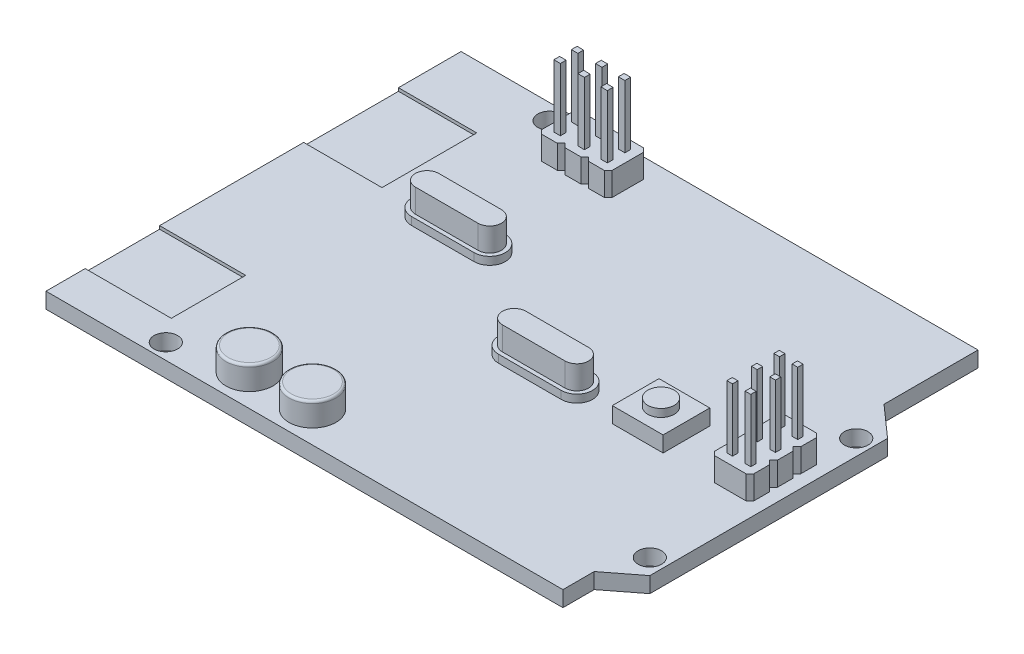
SolidWorks part; units mm, degrees
ref_plane "Front Plane" through (0, 0, 0) normal (0, 0, 1) x (1, 0, 0)
ref_plane "Top Plane" through (0, 0, 0) normal (0, 1, 0) x (1, 0, 0)
ref_plane "Right Plane" through (0, 0, 0) normal (1, 0, 0) x (0, 0, -1)
sketch "Sketch1" plane through (0, 0, 0) normal (0, 1, 0) x (1, 0, 0)
  line L0 (0, 0) -> (66, 0)
  line L1 (66, 0) -> (66, 4)
  line L2 (70, 7.1009) -> (70, 37.4502)
  line L3 (70, 37.4502) -> (66, 41)
  line L4 (66, 41) -> (66, 53)
  line L5 (66, 53) -> (0, 53)
  line L6 (0, 53) -> (0, 0)
  line L7 (66, 4) -> (70, 7.1009)
  point P4 (70, 7.1009)
  point P9 (70, 37.4502)
  dimension "D1" = 53
  dimension "D2" = 66
  dimension "D3" = 12
  dimension "D4" = 4
  dimension "D5" = 4
  dimension "D6" = 4
extrude "Boss-Extrude1" add sketch "Sketch1" along normal blind 2
sketch "Sketch2" plane through (0, 0, 0) normal (0, 1, 0) x (1, 0, 0)
  line L0 (70, 7.1009) -> (70, 37.4502) construction
  line L1 (0, 53) -> (0, 0) construction
  line L2 (0, 0) -> (66, 0) construction
  line L4 (66, 53) -> (0, 53) construction
  circle A0 centre (68, 35.4502) radius 1.5
  circle A1 centre (68, 9.1009) radius 1.5
  circle A2 centre (13.3, 2) radius 1.5
  circle A3 centre (13.3, 51) radius 1.5
  point P10 (0, 0)
  point P11 (0, 0)
  point P16 (0, 0)
  point P22 (0, 0)
  dimension "D1" = 3
  dimension "D4" = 3
  dimension "D5" = 3
  dimension "D6" = 3
  dimension "D2" = 2
  dimension "D3" = 2
  dimension "D7" = 13.3
  dimension "D8" = 2
  dimension "D9" = 2
  dimension "D10" = 2
  dimension "D11" = 2
  dimension "D12" = 13.3
extrude "Cut-Extrude2" cut sketch "Sketch2" against normal through all and the other way through all
sketch "Sketch3" plane through (0, 0, 0) normal (0, 1, 0) x (1, 0, 0)
  line L0 (0, 53) -> (0, 0) construction
  line L1 (0, 45) -> (10, 45)
  line L2 (0, 45) -> (0, 32.9)
  line L3 (0, 32.9) -> (10, 32.9)
  line L4 (10, 45) -> (10, 32.9)
  line L5 (66, 53) -> (0, 53) construction
  line L6 (0, 14.5) -> (11, 14.5)
  line L7 (0, 14.5) -> (0, 5)
  line L8 (0, 5) -> (11, 5)
  line L9 (11, 14.5) -> (11, 5)
  line L10 (0, 0) -> (66, 0) construction
  dimension "D1" = 10
  dimension "D2" = 12.1
  dimension "D3" = 8
  dimension "D4" = 11
  dimension "D5" = 9.5
  dimension "D6" = 5
extrude "Cut-Extrude7" cut sketch "Sketch3" against normal blind 0.4 from surface at 2 starting at face at (68, 2, -7.6009)
sketch "Sketch4" plane through (0, 2, 0) normal (0, 1, 0) x (1, 0, 0)
  line L0 (63.8799, 30.5) -> (63.3799, 30)
  line L1 (63.8799, 30.5) -> (67.8799, 30.5)
  line L2 (63.3799, 30) -> (63.3799, 28)
  line L3 (63.8799, 27.5) -> (67.8799, 27.5)
  line L4 (68.3799, 30) -> (68.3799, 28)
  line L5 (63.3799, 28) -> (63.8799, 27.5)
  line L6 (67.8799, 30.5) -> (68.3799, 30)
  line L7 (68.3799, 28) -> (67.8799, 27.5)
  line L8 (66, 53) -> (0, 53) construction
  line L9 (70, 7.1009) -> (70, 37.4502) construction
  point P12 (0, 0)
  point P13 (0, 0)
  dimension "D1" = 22.5
  dimension "D2" = 1.6201
extrude "Boss-Extrude2" add sketch "Sketch4" along normal blind 3
pattern_linear "LPattern1" count 3 spacing 3 along (0, 0, 1) of "Boss-Extrude2"
sketch "Sketch5" plane through (0, 5, 0) normal (0, 1, 0) x (1, 0, 0)
  line L0 (65.8799, 30.5) -> (65.8799, 26.0273) construction
  line L1 (64.3546, 29.2687) -> (65.0788, 29.2687)
  line L2 (64.3546, 29.2687) -> (64.3546, 28.579)
  line L3 (64.3546, 28.579) -> (65.0788, 28.579)
  line L4 (65.0788, 29.2687) -> (65.0788, 28.579)
  line L5 (67.8799, 30.5) -> (63.8799, 30.5) construction
  line L6 (63.8799, 27.5) -> (67.8799, 27.5) construction
  line L7 (66.681, 29.2687) -> (66.681, 28.579)
  line L8 (67.4052, 28.579) -> (66.681, 28.579)
  line L9 (67.4052, 29.2687) -> (67.4052, 28.579)
  line L10 (67.4052, 29.2687) -> (66.681, 29.2687)
  line L11 (67.4052, 25.7313) -> (66.681, 25.7313)
  line L12 (67.4052, 25.7313) -> (67.4052, 26.421)
  line L13 (67.4052, 26.421) -> (66.681, 26.421)
  line L14 (66.681, 25.7313) -> (66.681, 26.421)
  line L15 (65.0788, 25.7313) -> (65.0788, 26.421)
  line L16 (64.3546, 26.421) -> (65.0788, 26.421)
  line L17 (64.3546, 25.7313) -> (64.3546, 26.421)
  line L18 (64.3546, 25.7313) -> (65.0788, 25.7313)
  line L19 (63.8799, 24.5) -> (67.8799, 24.5) construction
  line L20 (66.681, 23.2687) -> (66.681, 22.579)
  line L21 (67.4052, 22.579) -> (66.681, 22.579)
  line L22 (67.4052, 23.2687) -> (67.4052, 22.579)
  line L23 (67.4052, 23.2687) -> (66.681, 23.2687)
  line L24 (64.3546, 23.2687) -> (65.0788, 23.2687)
  line L25 (64.3546, 23.2687) -> (64.3546, 22.579)
  line L26 (64.3546, 22.579) -> (65.0788, 22.579)
  line L27 (65.0788, 23.2687) -> (65.0788, 22.579)
extrude "Boss-Extrude4" add sketch "Sketch5" along normal blind 8
sketch "Sketch6" plane through (0, 2, 0) normal (0, 1, 0) x (1, 0, 0)
  line L0 (66, 53) -> (0, 53) construction
  line L1 (17.2829, 51) -> (19.2829, 51)
  line L2 (16.7829, 50.5) -> (16.7829, 46.5)
  line L3 (17.2829, 46) -> (19.2829, 46)
  line L4 (19.7829, 50.5) -> (19.7829, 46.5)
  line L5 (17.2829, 51) -> (16.7829, 50.5)
  line L6 (19.2829, 51) -> (19.7829, 50.5)
  line L7 (16.7829, 46.5) -> (17.2829, 46)
  line L8 (19.7829, 46.5) -> (19.2829, 46)
  point P14 (0, 0)
  point P15 (0, 0)
  point P18 (0, 0)
  dimension "D3" = 2
extrude "Boss-Extrude5" add sketch "Sketch6" along normal blind 3
pattern_linear "LPattern3" count 3 spacing 3 along (1, 0, 0) of "Boss-Extrude5"
sketch "Sketch8" plane through (0, 5, 0) normal (0, 1, 0) x (1, 0, 0)
  line L0 (16.7829, 48.5) -> (25.7829, 48.5) construction
  line L1 (16.7829, 50.5) -> (16.7829, 46.5) construction
  line L2 (25.7829, 46.5) -> (25.7829, 50.5) construction
  line L3 (19.7829, 50.5) -> (19.7829, 47.7652) construction
  line L4 (22.7829, 50.5) -> (22.7829, 47.637) construction
  line L5 (20.9065, 49.9848) -> (20.9065, 49.2538)
  line L6 (17.8296, 49.9848) -> (18.6593, 49.9848)
  line L7 (17.8296, 49.9848) -> (17.8296, 49.2538)
  line L8 (17.8296, 49.2538) -> (18.6593, 49.2538)
  line L9 (18.6593, 49.9848) -> (18.6593, 49.2538)
  line L10 (21.7363, 49.2538) -> (20.9065, 49.2538)
  line L11 (21.7363, 49.9848) -> (21.7363, 49.2538)
  line L12 (21.7363, 49.9848) -> (20.9065, 49.9848)
  line L13 (23.8296, 49.9848) -> (24.6593, 49.9848)
  line L14 (23.8296, 49.9848) -> (23.8296, 49.2538)
  line L15 (23.8296, 49.2538) -> (24.6593, 49.2538)
  line L16 (24.6593, 49.9848) -> (24.6593, 49.2538)
  line L17 (24.6593, 47.0152) -> (24.6593, 47.7462)
  line L18 (23.8296, 47.7462) -> (24.6593, 47.7462)
  line L19 (23.8296, 47.0152) -> (23.8296, 47.7462)
  line L20 (23.8296, 47.0152) -> (24.6593, 47.0152)
  line L21 (21.7363, 47.0152) -> (20.9065, 47.0152)
  line L22 (21.7363, 47.0152) -> (21.7363, 47.7462)
  line L23 (21.7363, 47.7462) -> (20.9065, 47.7462)
  line L24 (20.9065, 47.0152) -> (20.9065, 47.7462)
  line L25 (18.6593, 47.0152) -> (18.6593, 47.7462)
  line L26 (17.8296, 47.7462) -> (18.6593, 47.7462)
  line L27 (17.8296, 47.0152) -> (17.8296, 47.7462)
  line L28 (17.8296, 47.0152) -> (18.6593, 47.0152)
extrude "Boss-Extrude6" add sketch "Sketch8" along normal blind 8
sketch "Sketch9" plane through (0, 2, 0) normal (0, 1, 0) x (1, 0, 0)
  line L0 (63.8799, 21.5) -> (67.8799, 21.5) construction
  line L1 (50.8024, 27.4638) -> (57.2894, 27.4638)
  line L2 (50.8024, 27.4638) -> (50.8024, 21.5)
  line L3 (50.8024, 21.5) -> (57.2894, 21.5)
  line L4 (57.2894, 27.4638) -> (57.2894, 21.5)
extrude "Boss-Extrude7" add sketch "Sketch9" along normal blind 2
sketch "Sketch11" plane through (0, 4, 0) normal (0, 1, 0) x (1, 0, 0)
  circle A0 centre (54.0459, 24.4819) radius 1.6805
extrude "Boss-Extrude8" add sketch "Sketch11" along normal blind 1
sketch "Sketch12" plane through (0, 2, 0) normal (0, 1, 0) x (1, 0, 0)
  line L0 (36.8597, 22.9198) -> (44.8597, 22.9198) construction
  line L1 (36.8597, 24.9198) -> (44.8597, 24.9198)
  line L2 (36.8597, 20.9198) -> (44.8597, 20.9198)
  arc A0 (36.8597, 24.9198) -> (36.8597, 20.9198) centre (36.8597, 22.9198) ccw
  arc A1 (44.8597, 20.9198) -> (44.8597, 24.9198) centre (44.8597, 22.9198) ccw
  point P2 (40.8597, 22.9198)
  point P7 (40.8597, 22.9198)
  dimension "D1" = 8
  dimension "D2" = 4
extrude "Boss-Extrude9" add sketch "Sketch12" along normal blind 1
sketch "Sketch13" plane through (0, 3, 0) normal (0, 1, 0) x (1, 0, 0)
  line L4 (36.8597, 10.9198) -> (44.8597, 10.9198)
  line L5 (44.8597, 34.9198) -> (36.8597, 34.9198)
  line L6 (36.8597, 10.9198) -> (44.8597, 10.9198)
  line L7 (44.8597, 34.9198) -> (36.8597, 34.9198)
  line L10 (44.8597, 24.4198) -> (36.8597, 24.4198)
  line L11 (36.8597, 21.4198) -> (44.8597, 21.4198)
  line L12 (44.8597, 24.4198) -> (36.8597, 24.4198)
  line L13 (36.8597, 21.4198) -> (44.8597, 21.4198)
  arc A4 (36.8597, 34.9198) -> (36.8597, 10.9198) centre (36.8597, 22.9198) ccw
  arc A5 (44.8597, 10.9198) -> (44.8597, 34.9198) centre (44.8597, 22.9198) ccw
  arc A6 (36.8597, 34.9198) -> (36.8597, 10.9198) centre (36.8597, 22.9198) ccw
  arc A7 (44.8597, 10.9198) -> (44.8597, 34.9198) centre (44.8597, 22.9198) ccw
  arc A10 (44.8597, 21.4198) -> (44.8597, 24.4198) centre (44.8597, 22.9198) ccw
  arc A11 (36.8597, 24.4198) -> (36.8597, 21.4198) centre (36.8597, 22.9198) ccw
  arc A12 (44.8597, 21.4198) -> (44.8597, 24.4198) centre (44.8597, 22.9198) ccw
  arc A13 (36.8597, 24.4198) -> (36.8597, 21.4198) centre (36.8597, 22.9198) ccw
  dimension "D1" = 10
  dimension "D2" = 0.5
extrude "Boss-Extrude10" add sketch "Sketch13" along normal blind 3 contours L12 A13 L13 A12
sketch "Sketch14" plane through (0, 2, 0) normal (0, 1, 0) x (1, 0, 0)
  line L0 (16.0597, 32.5953) -> (24.0597, 32.5953) construction
  line L1 (16.0597, 34.5953) -> (24.0597, 34.5953)
  line L2 (16.0597, 30.5953) -> (24.0597, 30.5953)
  arc A0 (16.0597, 34.5953) -> (16.0597, 30.5953) centre (16.0597, 32.5953) ccw
  arc A1 (24.0597, 30.5953) -> (24.0597, 34.5953) centre (24.0597, 32.5953) ccw
  point P2 (20.0597, 32.5953)
  dimension "D1" = 8
  dimension "D2" = 4
extrude "Boss-Extrude11" add sketch "Sketch14" along normal blind 1
sketch "Sketch15" plane through (0, 3, 0) normal (0, 1, 0) x (1, 0, 0)
  line L0 (16.0597, 31.0953) -> (24.0597, 31.0953)
  line L1 (24.0597, 34.0953) -> (16.0597, 34.0953)
  line L2 (16.0597, 30.5953) -> (24.0597, 30.5953)
  line L3 (24.0597, 34.5953) -> (16.0597, 34.5953)
  line L4 (16.0597, 30.5953) -> (24.0597, 30.5953)
  line L5 (24.0597, 34.5953) -> (16.0597, 34.5953)
  arc A0 (16.0597, 34.0953) -> (16.0597, 31.0953) centre (16.0597, 32.5953) ccw
  arc A1 (24.0597, 31.0953) -> (24.0597, 34.0953) centre (24.0597, 32.5953) ccw
  arc A2 (16.0597, 34.5953) -> (16.0597, 30.5953) centre (16.0597, 32.5953) ccw
  arc A3 (24.0597, 30.5953) -> (24.0597, 34.5953) centre (24.0597, 32.5953) ccw
  arc A4 (16.0597, 34.5953) -> (16.0597, 30.5953) centre (16.0597, 32.5953) ccw
  arc A5 (24.0597, 30.5953) -> (24.0597, 34.5953) centre (24.0597, 32.5953) ccw
  dimension "D1" = 0
  dimension "D2" = 0.5
extrude "Boss-Extrude12" add sketch "Sketch15" along normal blind 3 contours L0 A1 L1 A0
sketch "Sketch16" plane through (0, 2, 0) normal (0, 1, 0) x (1, 0, 0)
  line L1 (0, 0) -> (66, 0) construction
  circle A0 centre (21.9692, 4) radius 3
  circle A1 centre (30.0251, 4) radius 3
  point P4 (21.9692, 4.1988)
  point P5 (31.4956, 4.1988)
  point P8 (30.0251, 4)
  dimension "D1" = 6
  dimension "D2" = 6
  dimension "D3" = 4
extrude "Boss-Extrude13" add sketch "Sketch16" along normal blind 3
fillet "Fillet1" radius 0.3 2 edges at (30.0251, 5, -1) (21.9692, 5, -1)
